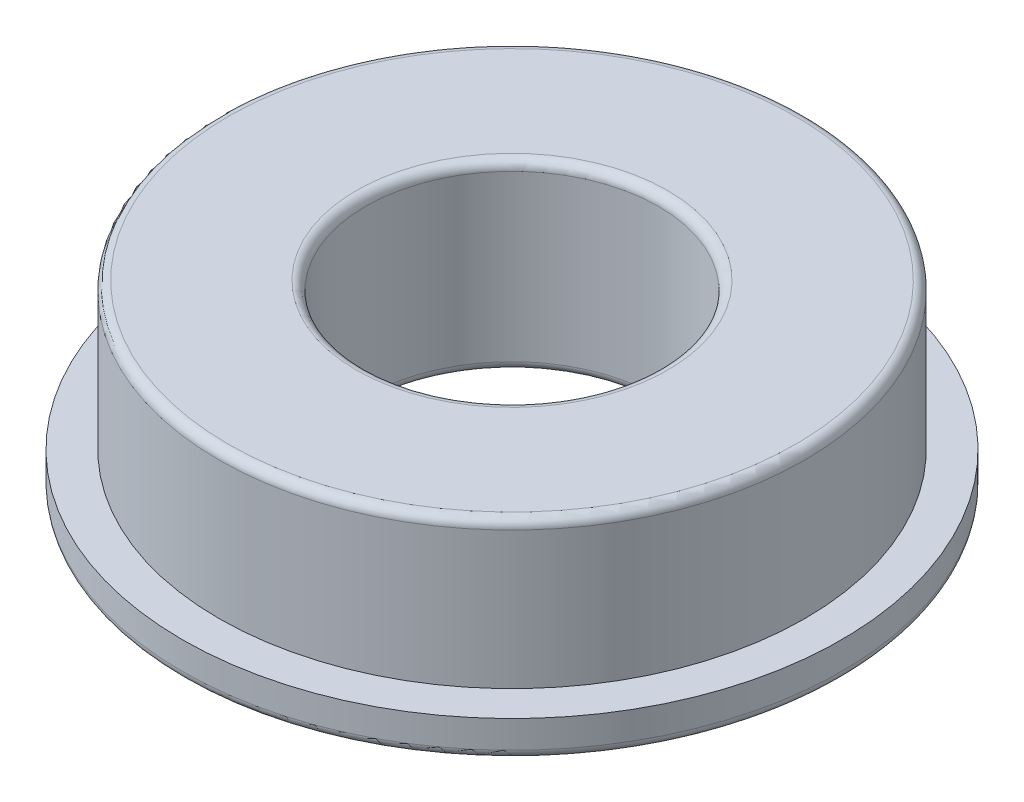
SolidWorks part; units mm, degrees
ref_plane "Front" through (0, 0, 0) normal (0, 0, 1) x (1, 0, 0)
ref_plane "Top" through (0, 0, 0) normal (0, 1, 0) x (1, 0, 0)
ref_plane "Right" through (0, 0, 0) normal (1, 0, 0) x (0, 0, -1)
sketch "Esquisse1" plane through (0, 0, 0) normal (0, 0, 1) x (1, 0, 0)
  line L0 (0, 0) -> (0, 15.7391) construction
  line L1 (4, 5) -> (4, 0)
  line L2 (4, 0) -> (9, 0)
  line L3 (9, 0) -> (9, 1)
  line L4 (9, 1) -> (8, 1)
  line L5 (8, 1) -> (8, 5)
  line L6 (8, 5) -> (4, 5)
  dimension "D1" = 8
  dimension "D2" = 18
  dimension "D3" = 16
  dimension "D4" = 5
  dimension "D5" = 1
revolve "Révolution1" add sketch "Esquisse1" angle 360 about L0
fillet "Congé1" radius 0.25 4 edges at (0, 0, -4) (0, 0, -9) (0, 5, -8) (0, 5, -4)
